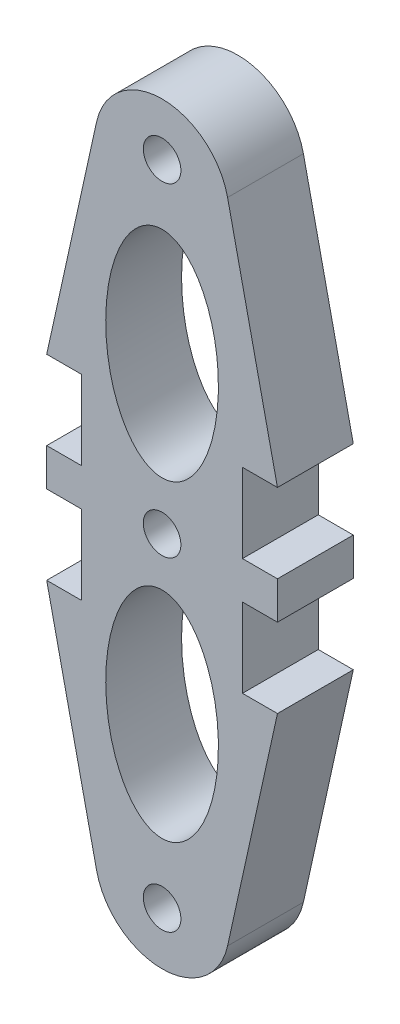
SolidWorks part; units mm, degrees
material "Acrylic (Medium-high impact)"
ref_plane "Front Plane" through (0, 0, 0) normal (0, 0, 1) x (1, 0, 0)
ref_plane "Top Plane" through (0, 0, 0) normal (0, 1, 0) x (1, 0, 0)
ref_plane "Right Plane" through (0, 0, 0) normal (1, 0, 0) x (0, 0, -1)
sketch "Sketch1" plane through (0, 0, 0) normal (0, 0, 1) x (1, 0, 0)
  line L0 (-213.0408, 464.8524) -> (49786.9592, 464.8524) construction
  line L1 (781.4592, 464.8524) -> (778.7592, 464.8524)
  line L2 (781.4592, 464.8524) -> (781.4592, 470.9524)
  line L3 (781.4592, 470.9524) -> (778.7592, 470.9524)
  line L4 (787.6592, -515.9255) -> (787.6592, 49484.0745) construction
  line L5 (-215.2208, 463.4024) -> (49784.7792, 463.4024) construction
  line L6 (793.8592, 470.9524) -> (793.8592, 488.4024) construction
  line L7 (-217.5077, 461.9524) -> (49782.4923, 461.9524) construction
  line L8 (786.2092, -537.0976) -> (786.2092, 49462.9024) construction
  line L9 (789.1092, -536.5976) -> (789.1092, 49463.4024) construction
  line L10 (793.8592, 464.8524) -> (796.5592, 464.8524)
  line L11 (781.4592, 470.9524) -> (793.8592, 470.9524) construction
  line L12 (793.8592, 470.9524) -> (796.5592, 470.9524)
  line L13 (793.8592, 464.8524) -> (793.8592, 470.9524)
  line L14 (778.7592, 464.8524) -> (778.7592, 461.9524)
  line L15 (796.5592, 464.8524) -> (796.5592, 461.9524)
  line L16 (786.2092, 488.4024) -> (782.6065, 488.4024) construction
  line L17 (781.4592, 461.9524) -> (778.7592, 461.9524)
  line L18 (793.8592, 470.9524) -> (793.1379, 470.9192) construction
  line L19 (781.4592, 455.8524) -> (778.7592, 455.8524)
  line L20 (781.4592, 461.9524) -> (781.4592, 455.8524)
  line L21 (793.8592, 461.9524) -> (796.5592, 461.9524)
  line L22 (793.8592, 461.9524) -> (793.8592, 455.8524)
  line L23 (793.8592, 455.8524) -> (796.5592, 455.8524)
  line L24 (778.7592, 470.9524) -> (782.6065, 488.4024)
  line L25 (792.7118, 488.4024) -> (796.5592, 470.9524)
  line L26 (792.7118, 438.4024) -> (796.5592, 455.8524)
  line L27 (789.1092, 438.4024) -> (792.7118, 438.4024) construction
  line L28 (786.2092, 438.4024) -> (782.6065, 438.4024) construction
  line L29 (778.7592, 455.8524) -> (782.6065, 438.4024)
  line L35 (789.1092, 488.4024) -> (792.7118, 488.4024) construction
  arc A0 (782.6065, 488.4024) -> (792.7118, 488.4024) centre (787.6592, 487.2884) cw
  arc A1 (782.6065, 438.4024) -> (792.7118, 438.4024) centre (787.6592, 439.5164) ccw
  circle A3 centre (787.6592, 488.4024) radius 1.45
  circle A5 centre (787.6592, 438.4024) radius 1.45
  circle A6 centre (787.6592, 463.4024) radius 1.45
  ellipse E0 centre (787.6592, 475.4481) end of major axis (787.6592, 483.7502) minor radius 4.3465
  ellipse E1 centre (787.6592, 451.3566) end of major axis (787.6592, 443.0545) minor radius 4.3465
  point P10 (778.7592, 463.4024)
  point P19 (796.5592, 463.4024)
  dimension "D1" = 2.9
  dimension "D3" = 6.1
  dimension "D10" = 5.174
  dimension "D2" = 2.7
  dimension "D4" = 25
  dimension "D5" = 12.4
  dimension "D6" = 16.6042
  dimension "D7" = 8.693
  dimension "D8" = 2.2937
  dimension "D9" = 17.45
extrude "Boss-Extrude1" add sketch "Sketch1" along normal blind 5.85
